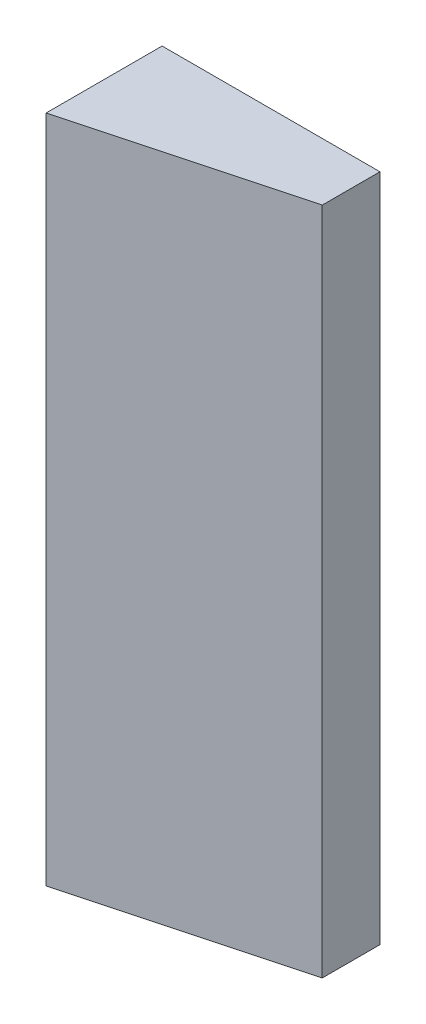
SolidWorks part; units mm, degrees
ref_plane "Front Plane" through (0, 0, 0) normal (0, 0, 1) x (1, 0, 0)
ref_plane "Top Plane" through (0, 0, 0) normal (0, 1, 0) x (1, 0, 0)
ref_plane "Right Plane" through (0, 0, 0) normal (1, 0, 0) x (0, 0, -1)
sketch "Sketch1" plane through (0, 0, 0) normal (0, 0, 1) x (1, 0, 0)
  line L1 (-7.55, -23.2) -> (7.55, -23.2)
  line L2 (-7.55, -23.2) -> (-7.55, 23.2)
  line L3 (-7.55, 23.2) -> (7.55, 23.2)
  line L4 (7.55, -23.2) -> (7.55, 23.2)
  line L5 (-7.55, -23.2) -> (7.55, 23.2) construction
  line L6 (-7.55, 23.2) -> (7.55, -23.2) construction
  line L7 (-4.55, -20.2) -> (4.55, -20.2)
  line L8 (-4.55, -20.2) -> (-4.55, 20.2)
  line L9 (-4.55, 20.2) -> (4.55, 20.2)
  line L10 (4.55, -20.2) -> (4.55, 20.2)
  line L11 (-4.55, -20.2) -> (4.55, 20.2) construction
  line L12 (-4.55, 20.2) -> (4.55, -20.2) construction
  point P0 (0, 0)
  point P6 (0, 0)
  dimension "D1" = 3
  dimension "D2" = 40.4
  dimension "D3" = 9.1
  dimension "D4" = 3
extrude "Boss-Extrude1" add sketch "Sketch1" along normal blind 4 contours L7 L10 L9 L8 | L1 L4 L3 L2 L10 L7 L8 L9
sketch "Sketch2" plane through (0, 0, 4) normal (0, 0, 1) x (1, 0, 0)
  line L1 (-4.55, -20.2) -> (4.55, -20.2)
  line L2 (-4.55, -20.2) -> (-4.55, 20.2)
  line L3 (-4.55, 20.2) -> (4.55, 20.2)
  line L4 (4.55, -20.2) -> (4.55, 20.2)
  line L5 (-4.55, -20.2) -> (4.55, 20.2) construction
  line L6 (-4.55, 20.2) -> (4.55, -20.2) construction
  point P0 (0, 0)
  dimension "D1" = 9.1
  dimension "D2" = 40.4
hole_wizard "Tap Drill for M2x0.4 Tap1" positions "3DSketch1" profile "Sketch3" hole size "M2x0.4" standard "ANSI Metric"
sketch3d "3DSketch1"
  point P0 (-4.55, 20.2, 4)
  point P3 (4.55, 20.2, 4)
  point P6 (4.55, -20.2, 4)
  point P9 (-4.55, -20.2, 4)
sketch "Sketch3" plane through (-4.55, 20.2, 4) normal (1, 0, 0) x (0, -1, 0)
  line L0 (0, 0) -> (0, 10.5408)
  line L1 (0, 10.5408) -> (0.9, 10)
  line L2 (0.9, 10) -> (0.9, 0)
  line L5 (0.9, 0) -> (0, 0)
  line L10 (0, 10.5408) -> (-0.9, 10) construction
  line L11 (0, -6.35) -> (0, 107.95) construction
  dimension "Hole Dia." = 1.8
  dimension "Hole Depth" = 10
  dimension "Drill Angle" = 118
sketch "Sketch5" plane through (0, -23.2, 0) normal (0, -1, 0) x (-1, 0, 0)
  line L0 (-7.55, -4) -> (7.55, -8.046)
  line L1 (7.55, -8.046) -> (7.55, -4)
  line L2 (7.55, -4) -> (7.55, 0) construction
  line L4 (7.55, -4) -> (-7.55, -4) construction
  line L5 (-7.55, -4) -> (7.55, -4)
  dimension "D1" = 15
extrude "Boss-Extrude2" add sketch "Sketch5" against normal up to surface (46.4 mm away) up to face at (0, 23.2, 2)
